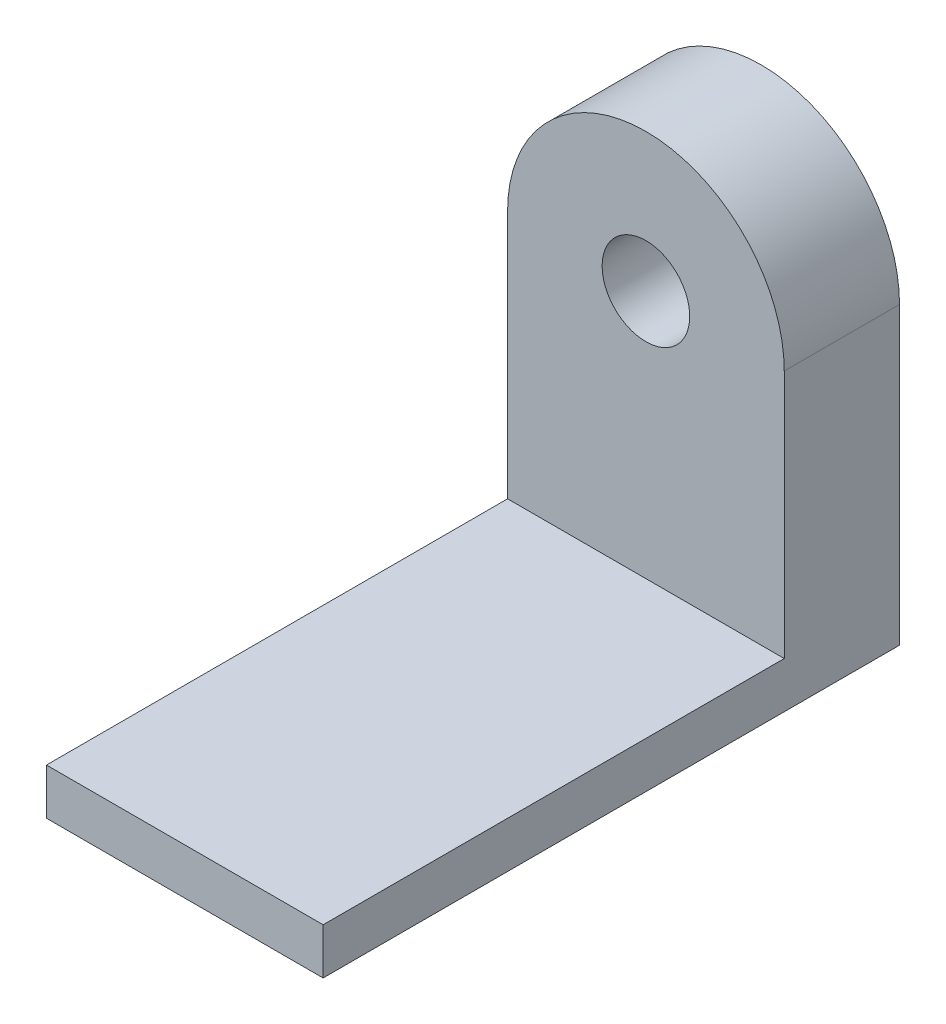
SolidWorks part; units mm, degrees
ref_plane "Front Plane" through (0, 0, 0) normal (0, 0, 1) x (1, 0, 0)
ref_plane "Top Plane" through (0, 0, 0) normal (0, 1, 0) x (1, 0, 0)
ref_plane "Right Plane" through (0, 0, 0) normal (1, 0, 0) x (0, 0, -1)
sketch "Sketch1" plane through (0, 0, 0) normal (0, 1, 0) x (1, 0, 0)
  line L1 (0, 0) -> (60, 0)
  line L2 (0, 0) -> (0, 125)
  line L3 (0, 125) -> (60, 125)
  line L4 (60, 0) -> (60, 125)
  dimension "D1" = 125
  dimension "D2" = 60
extrude "Boss-Extrude1" add sketch "Sketch1" along normal blind 10
sketch "Sketch2" plane through (0, 0, -125) normal (0, 0, -1) x (-1, 0, 0)
  line L0 (-60, 0) -> (0, 0) construction
  line L1 (-60, 10) -> (0, 10)
  line L2 (-60, 10) -> (-60, 64)
  line L3 (0, 10) -> (0, 0) construction
  line L4 (0, 10) -> (0, 64)
  arc A0 (0, 64) -> (-60, 64) centre (-30, 64) ccw
  circle A1 centre (-30, 64) radius 9.5
  dimension "D2" = 19
  dimension "D1" = 64
extrude "Boss-Extrude2" add sketch "Sketch2" against normal blind 25
